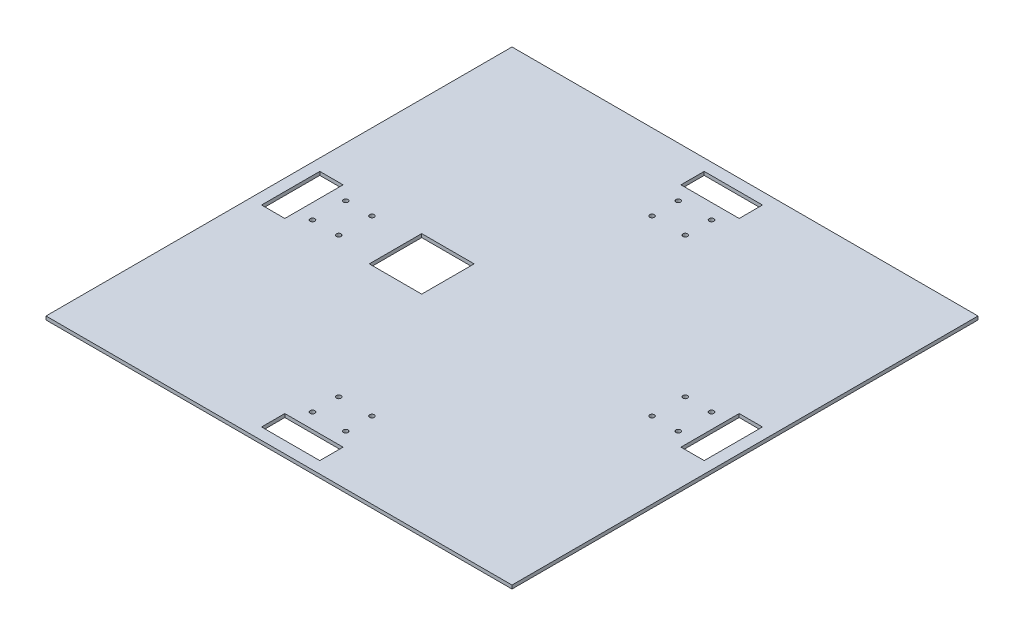
SolidWorks part; units mm, degrees
ref_plane "前视" through (0, 0, 0) normal (0, 0, 1) x (1, 0, 0)
ref_plane "上视" through (0, 0, 0) normal (0, 1, 0) x (1, 0, 0)
ref_plane "右视" through (0, 0, 0) normal (1, 0, 0) x (0, 0, -1)
sketch "Sketch1" plane through (0, 0, 0) normal (0, 1, 0) x (1, 0, 0)
  line L0 (200, 400) -> (200, -91.6949) construction
  line L1 (0, 0) -> (400, 0)
  line L2 (0, 0) -> (0, 400)
  line L3 (0, 400) -> (400, 400)
  line L4 (400, 0) -> (400, 400)
  line L5 (0, 200) -> (534.7225, 200) construction
  line L6 (10, 225) -> (10, 175)
  line L7 (175, 30) -> (225, 30)
  line L8 (175, 30) -> (175, 10)
  line L9 (175, 10) -> (225, 10)
  line L10 (225, 30) -> (225, 10)
  line L11 (30, 225) -> (10, 225)
  line L12 (30, 175) -> (10, 175)
  line L13 (30, 225) -> (30, 175)
  line L14 (225, 390) -> (175, 390)
  line L15 (225, 370) -> (225, 390)
  line L16 (175, 370) -> (175, 390)
  line L17 (225, 370) -> (175, 370)
  line L18 (390, 175) -> (390, 225)
  line L19 (370, 175) -> (390, 175)
  line L20 (370, 225) -> (390, 225)
  line L21 (370, 175) -> (370, 225)
  line L23 (145, 222.5) -> (100, 222.5)
  line L24 (145, 222.5) -> (145, 177.5)
  line L25 (145, 177.5) -> (100, 177.5)
  line L26 (100, 222.5) -> (100, 177.5)
  circle A0 centre (185.75, 43) radius 2
  circle A1 centre (185.75, 65.5) radius 2
  circle A2 centre (214.25, 65.5) radius 2
  circle A3 centre (214.25, 43) radius 2
  circle A4 centre (43, 214.25) radius 2
  circle A5 centre (65.5, 214.25) radius 2
  circle A6 centre (65.5, 185.75) radius 2
  circle A7 centre (43, 185.75) radius 2
  circle A8 centre (214.25, 357) radius 2
  circle A9 centre (214.25, 334.5) radius 2
  circle A10 centre (185.75, 334.5) radius 2
  circle A11 centre (185.75, 357) radius 2
  circle A12 centre (357, 185.75) radius 2
  circle A13 centre (334.5, 185.75) radius 2
  circle A14 centre (334.5, 214.25) radius 2
  circle A15 centre (357, 214.25) radius 2
  point P21 (200, 200)
  point P61 (200, 200)
  dimension "D7" = 13
  dimension "D8" = 14.25
  dimension "D11" = 4
  dimension "D1" = 400
  dimension "D2" = 400
  dimension "D3" = 20
  dimension "D4" = 50
  dimension "D5" = 25
  dimension "D6" = 10
  dimension "D9" = 35.5
  dimension "D12" = 14.25
  dimension "D13" = 45
  dimension "D14" = 45
  dimension "D15" = 22.5
  dimension "D16" = 100
  dimension "D10" = 4
extrude "Extrude1" add sketch "Sketch1" along normal blind 3
